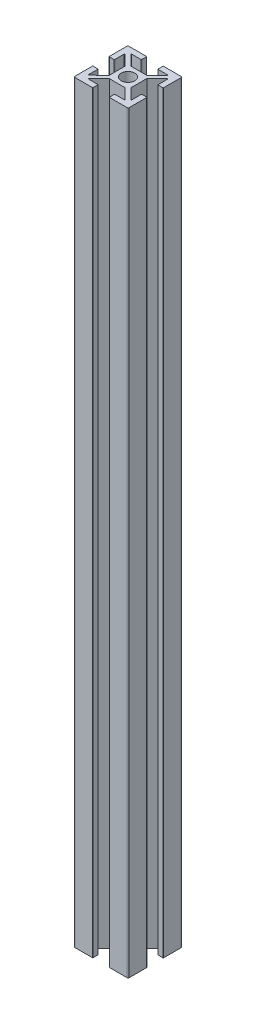
SolidWorks part; units mm, degrees
ref_plane "Front Plane" through (0, 0, 0) normal (0, 0, 1) x (1, 0, 0)
ref_plane "Top Plane" through (0, 0, 0) normal (0, 1, 0) x (1, 0, 0)
ref_plane "Right Plane" through (0, 0, 0) normal (1, 0, 0) x (0, 0, -1)
sketch "Sketch1" plane through (0, 0, 0) normal (0, 1, 0) x (1, 0, 0)
  line L0 (-9.8963, 3) -> (-8.1963, 3)
  line L3 (-3.1963, 10) -> (-9.6963, 10)
  line L4 (-10.0463, 3.15) -> (-10.0463, 9.65)
  line L7 (2.9332, 4) -> (-2.9332, 4)
  line L8 (-4, -2.9454) -> (-4, 2.9454)
  line L9 (-8.0463, 3.15) -> (-8.0463, 6.5862)
  line L10 (-6.6144, 8) -> (-3.1963, 8)
  line L11 (-3.0463, 8.15) -> (-3.0463, 9.85)
  line L12 (-8.0463, 8) -> (-4, 4) construction
  line L13 (-7.7908, 6.6929) -> (-4, 2.9454)
  line L14 (-6.7198, 7.7433) -> (-2.9332, 4)
  line L15 (8.0463, 8) -> (4, 4) construction
  line L22 (0, 0) -> (0, 11.6886) construction
  line L25 (0, 0) -> (-14.9841, 0) construction
  line L27 (6.7198, 7.7433) -> (2.9332, 4)
  line L28 (7.7908, 6.6929) -> (4, 2.9454)
  line L46 (3.0463, 8.15) -> (3.0463, 9.85)
  line L47 (6.6144, 8) -> (3.1963, 8)
  line L48 (8.0463, 3.15) -> (8.0463, 6.5862)
  line L49 (4, -2.9454) -> (4, 2.9454)
  line L50 (10.0463, 3.15) -> (10.0463, 9.65)
  line L51 (3.1963, 10) -> (9.6963, 10)
  line L52 (9.8963, 3) -> (8.1963, 3)
  line L53 (8.0463, -8) -> (4, -4) construction
  line L54 (-8.0463, -8) -> (-4, -4) construction
  line L55 (9.8963, -3) -> (8.1963, -3)
  line L56 (3.1963, -10) -> (9.6963, -10)
  line L57 (10.0463, -3.15) -> (10.0463, -9.65)
  line L58 (8.0463, -3.15) -> (8.0463, -6.5862)
  line L59 (6.6144, -8) -> (3.1963, -8)
  line L60 (3.0463, -8.15) -> (3.0463, -9.85)
  line L61 (7.7908, -6.6929) -> (4, -2.9454)
  line L62 (6.7198, -7.7433) -> (2.9332, -4)
  line L63 (-6.7198, -7.7433) -> (-2.9332, -4)
  line L64 (-7.7908, -6.6929) -> (-4, -2.9454)
  line L65 (-3.0463, -8.15) -> (-3.0463, -9.85)
  line L66 (-6.6144, -8) -> (-3.1963, -8)
  line L67 (-8.0463, -3.15) -> (-8.0463, -6.5862)
  line L68 (2.9332, -4) -> (-2.9332, -4)
  line L69 (-10.0463, -3.15) -> (-10.0463, -9.65)
  line L70 (-3.1963, -10) -> (-9.6963, -10)
  line L71 (-9.8963, -3) -> (-8.1963, -3)
  circle A0 centre (0, 0) radius 2.5
  arc A1 (-10.0463, 9.65) -> (-9.6963, 10) centre (-9.6963, 9.65) cw
  arc A2 (-9.8963, 3) -> (-10.0463, 3.15) centre (-9.8963, 3.15) cw
  arc A3 (-8.1963, 3) -> (-8.0463, 3.15) centre (-8.1963, 3.15) ccw
  arc A4 (-3.1963, 10) -> (-3.0463, 9.85) centre (-3.1963, 9.85) cw
  arc A5 (-3.1963, 8) -> (-3.0463, 8.15) centre (-3.1963, 8.15) ccw
  arc A6 (-6.7198, 7.7433) -> (-6.6144, 8) centre (-6.6144, 7.85) cw
  arc A7 (-7.7908, 6.6929) -> (-8.0463, 6.5862) centre (-7.8963, 6.5862) ccw
  arc A8 (7.7908, 6.6929) -> (8.0463, 6.5862) centre (7.8963, 6.5862) cw
  arc A9 (6.7198, 7.7433) -> (6.6144, 8) centre (6.6144, 7.85) ccw
  arc A10 (3.1963, 8) -> (3.0463, 8.15) centre (3.1963, 8.15) cw
  arc A11 (3.1963, 10) -> (3.0463, 9.85) centre (3.1963, 9.85) ccw
  arc A12 (8.1963, 3) -> (8.0463, 3.15) centre (8.1963, 3.15) cw
  arc A13 (9.8963, 3) -> (10.0463, 3.15) centre (9.8963, 3.15) ccw
  arc A14 (10.0463, 9.65) -> (9.6963, 10) centre (9.6963, 9.65) ccw
  arc A15 (10.0463, -9.65) -> (9.6963, -10) centre (9.6963, -9.65) cw
  arc A16 (9.8963, -3) -> (10.0463, -3.15) centre (9.8963, -3.15) cw
  arc A17 (8.1963, -3) -> (8.0463, -3.15) centre (8.1963, -3.15) ccw
  arc A18 (3.1963, -10) -> (3.0463, -9.85) centre (3.1963, -9.85) cw
  arc A19 (3.1963, -8) -> (3.0463, -8.15) centre (3.1963, -8.15) ccw
  arc A20 (6.7198, -7.7433) -> (6.6144, -8) centre (6.6144, -7.85) cw
  arc A21 (7.7908, -6.6929) -> (8.0463, -6.5862) centre (7.8963, -6.5862) ccw
  arc A22 (-7.7908, -6.6929) -> (-8.0463, -6.5862) centre (-7.8963, -6.5862) cw
  arc A23 (-6.7198, -7.7433) -> (-6.6144, -8) centre (-6.6144, -7.85) ccw
  arc A24 (-3.1963, -8) -> (-3.0463, -8.15) centre (-3.1963, -8.15) cw
  arc A25 (-3.1963, -10) -> (-3.0463, -9.85) centre (-3.1963, -9.85) ccw
  arc A26 (-8.1963, -3) -> (-8.0463, -3.15) centre (-8.1963, -3.15) cw
  arc A27 (-9.8963, -3) -> (-10.0463, -3.15) centre (-9.8963, -3.15) ccw
  arc A28 (-10.0463, -9.65) -> (-9.6963, -10) centre (-9.6963, -9.65) ccw
  point P8 (-10.0463, 10)
  point P27 (-10.0463, 3)
  point P30 (3.0463, 8)
  point P31 (10.0463, -10)
  point P50 (4, 0)
  point P55 (-8.0463, 3)
  point P58 (-3.0463, 10)
  point P61 (-3.0463, 8)
  point P63 (0, 4)
  point P65 (3.0463, 10)
  point P66 (8.0463, 3)
  point P67 (10.0463, 3)
  point P68 (10.0463, 10)
  point P118 (-4, 0)
  point P119 (10.0463, -3)
  point P120 (8.0463, -3)
  point P121 (3.0463, -10)
  point P122 (0, -4)
  point P123 (-3.0463, -8)
  point P124 (-3.0463, -10)
  point P125 (-8.0463, -3)
  point P126 (3.0463, -8)
  point P127 (-10.0463, -3)
  point P128 (-10.0463, -10)
  dimension "D2" = 0.35
  dimension "D3" = 0.15
  dimension "D4" = 0.15
  dimension "D5" = 0.15
  dimension "D12" = 0.15
  dimension "D13" = 0.15
  dimension "D14" = 0.15
  dimension "D6" = 2
  dimension "D7" = 7
  dimension "D8" = 7
  dimension "D9" = 2
  dimension "D10" = 0.75
  dimension "D11" = 0.75
extrude "Boss-Extrude2" add sketch "Sketch1" along normal blind 279
